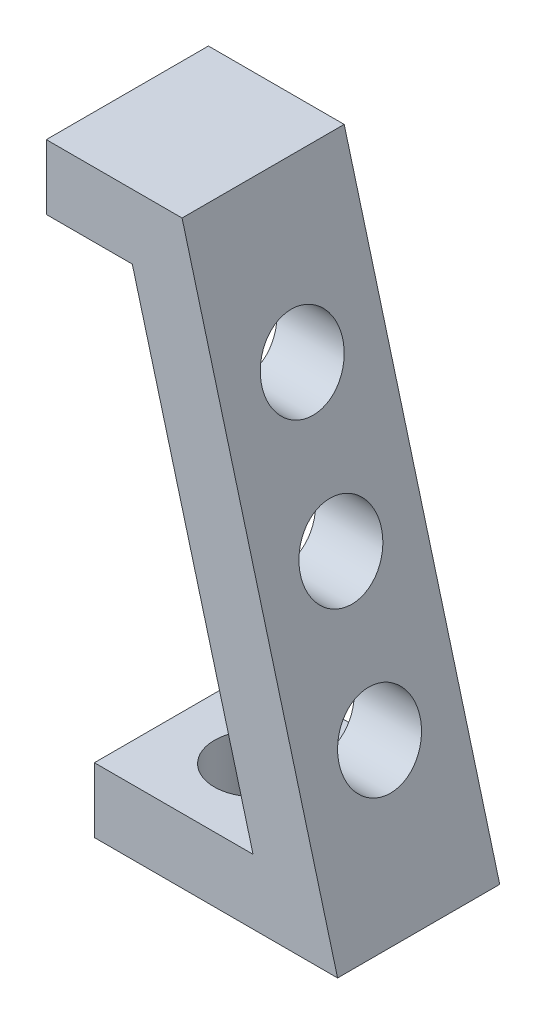
SolidWorks part; units mm, degrees
ref_plane "Front Plane" through (0, 0, 0) normal (0, 0, 1) x (1, 0, 0)
ref_plane "Top Plane" through (0, 0, 0) normal (0, 1, 0) x (1, 0, 0)
ref_plane "Right Plane" through (0, 0, 0) normal (1, 0, 0) x (0, 0, -1)
sketch "Sketch1" plane through (0, 0, 0) normal (0, 0, 1) x (1, 0, 0)
  line L0 (-6.069, -4) -> (8.931, -4)
  line L1 (8.931, -4) -> (-0.6615, 31.8)
  line L3 (-3.7315, 27.8023) -> (3.7181, 0)
  line L4 (3.7181, 0) -> (-6.069, 0)
  line L5 (-6.069, 0) -> (-6.069, -4)
  line L6 (-0.6615, 31.8) -> (-9.0362, 31.8)
  line L7 (-9.0362, 31.8) -> (-9.0362, 27.8023)
  line L8 (-9.0362, 27.8023) -> (-3.7315, 27.8023)
  dimension "D1" = 4
  dimension "D3" = 35.8
  dimension "D4" = 15
  dimension "D5" = 15
extrude "Boss-Extrude1" add sketch "Sketch1" along normal blind 10
sketch "Sketch2" plane through (-6.069, 0, 0) normal (-1, 0, 0) x (0, 0, 1)
  line L0 (10, 0) -> (0, 0) construction
  line L1 (10, 27.8023) -> (0, 27.8023) construction
  circle A0 centre (5, 22.8023) radius 2.5
  circle A2 centre (5, 5) radius 2.5
  circle A3 centre (5, 13.9) radius 2.5
  dimension "D2" = 5
  dimension "D4" = 5
  dimension "D5" = 5
  dimension "D1" = 5
  dimension "D6" = 5
  dimension "D7" = 8.9
extrude "Cut-Extrude1" cut sketch "Sketch2" against normal blind 15 and the other way blind 10
sketch "Sketch3" plane through (0, 0, 0) normal (0, 1, 0) x (1, 0, 0)
  line L0 (-6.069, -10) -> (-6.069, 0) construction
  circle A0 centre (-1.069, -5.1005) radius 2.5
  dimension "D1" = 5
  dimension "D2" = 5
extrude "Cut-Extrude2" cut sketch "Sketch3" against normal blind 15
